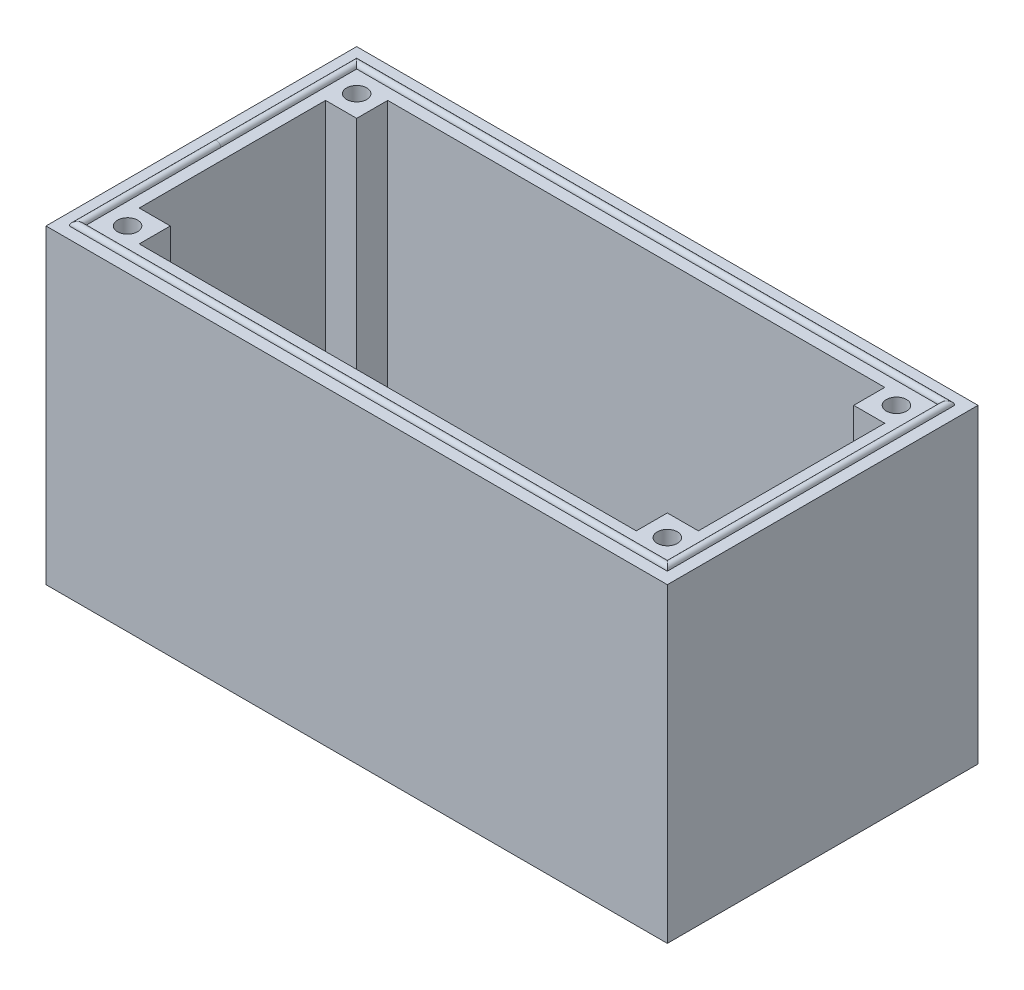
SolidWorks part; units mm, degrees
ref_plane "Piano frontale" through (0, 0, 0) normal (0, 0, 1) x (1, 0, 0)
ref_plane "Piano superiore" through (0, 0, 0) normal (0, 1, 0) x (1, 0, 0)
ref_plane "Piano destro" through (0, 0, 0) normal (1, 0, 0) x (0, 0, -1)
sketch "Schizzo1" plane through (0, 0, 0) normal (0, 0, 1) x (1, 0, 0)
  line L0 (0, 0) -> (0, 20)
  line L1 (0, 20) -> (40, 20)
  line L2 (40, 20) -> (40, 0)
  line L3 (40, 0) -> (0, 0)
  dimension "D1" = 40
  dimension "D2" = 20
extrude "Estrusione-Estrusione1" add sketch "Schizzo1" against normal blind 20
sketch "Schizzo2" plane through (0, 20, 0) normal (0, 1, 0) x (1, 0, 0)
  line L0 (0, 10) -> (40, 10) construction
  line L1 (0, 20) -> (0, 0) construction
  line L2 (40, 20) -> (40, 0) construction
  line L3 (20, 20) -> (20, 0) construction
  line L4 (40, 20) -> (0, 20) construction
  line L5 (40, 0) -> (0, 0) construction
  line L6 (4, 18) -> (4, 16)
  line L7 (36, 2) -> (4, 2)
  line L8 (38, 4) -> (38, 16)
  line L9 (36, 18) -> (4, 18)
  line L10 (2, 4) -> (2, 16)
  line L13 (4, 16) -> (2, 16)
  line L14 (2, 4) -> (4, 4)
  line L15 (4, 4) -> (4, 2)
  line L16 (36, 18) -> (36, 16)
  line L17 (36, 16) -> (38, 16)
  line L18 (38, 4) -> (36, 4)
  line L19 (36, 4) -> (36, 2)
  point P12 (20, 10)
  point P16 (36, 17.1111)
  point P30 (36, 4)
  dimension "D1" = 2
  dimension "D2" = 2
  dimension "D3" = 2
  dimension "D4" = 12
  dimension "D5" = 32
extrude "Taglio-Estrusione1" cut sketch "Schizzo2" against normal blind 20 contours L8 L17 L16 L9 L6 L13 L10 L14 L15 L7 L19 L18
ref_plane "Piano1" through (0, 0, -10) normal (0, 0, 1) x (1, 0, 0)
sketch "Schizzo3" plane through (0, 0, -10) normal (0, 0, 1) x (1, 0, 0)
  line L0 (40, 20) -> (0, 20) construction
  line L1 (0.75, 20) -> (1.25, 20)
  arc A0 (1.25, 20) -> (0.75, 20) centre (1, 20) ccw
  point P0 (1.999, 20)
  dimension "D1" = 0.5
  dimension "D2" = 1
  dimension "D3" = 0.999
sketch "Schizzo4" plane through (0, 20, 0) normal (0, 1, 0) x (1, 0, 0)
  line L0 (0, 10) -> (40, 10) construction
  line L1 (0, 20) -> (0, 0) construction
  line L2 (-11.1375, 10) -> (11.1375, 10) construction
  line L3 (20, 0) -> (20, 20) construction
  line L4 (40, 0) -> (0, 0) construction
  line L5 (40, 20) -> (0, 20) construction
  line L6 (40, 20) -> (40, 0) construction
  line L7 (1, 19) -> (39, 19)
  line L8 (1, 19) -> (1, 1)
  line L9 (1, 1) -> (39, 1)
  line L10 (39, 19) -> (39, 1)
  line L11 (1, 19) -> (39, 1) construction
  line L12 (1, 1) -> (39, 19) construction
  point P12 (20, 10)
  dimension "D1" = 1
  dimension "D2" = 1
  dimension "D3" = 1
sweep "Sweep1" add profiles "Schizzo3" path "Schizzo4"
sketch "Schizzo5" plane through (0, 0, 0) normal (0, -1, 0) x (1, 0, 0)
  line L4 (1, -19) -> (39, -19)
  line L5 (1, -1) -> (1, -19)
  line L6 (39, -1) -> (1, -1)
  line L7 (39, -19) -> (39, -1)
  line L8 (1, -19) -> (39, -19)
  line L9 (1, -1) -> (1, -19)
  line L10 (39, -1) -> (1, -1)
  line L11 (39, -19) -> (39, -1)
  dimension "D1" = 0
sketch "Schizzo6" plane through (0, 0, -10) normal (0, 0, 1) x (1, 0, 0)
  line L0 (39, 0) -> (1, 0) construction
  line L1 (1, 0) -> (39, 0) construction
  line L2 (0, 20) -> (0, 0) construction
  line L3 (0.75, 0) -> (1.25, 0)
  arc A0 (1.25, 0) -> (0.75, 0) centre (1, 0) ccw
  dimension "D1" = 0.5
  dimension "D2" = 1
sweep "Taglia-Sweep1" cut profiles "Schizzo6" path "Schizzo5"
hole_wizard "Foro per Vite M1-1" positions "Schizzo7" profile "Schizzo9" hole size "M1" standard "KS" end condition through all
sketch "Schizzo7" plane through (0, 0, 0) normal (0, -1, 0) x (-1, 0, 0)
  line L4 (-38.75, 1.25) -> (-38.75, 18.75) construction
  line L5 (-38.75, 18.75) -> (-1.25, 18.75) construction
  point P0 (-37.375, 17.375)
  dimension "D1" = 1.375
  dimension "D2" = 1.375
sketch "Schizzo9" plane through (37.375, 0, -17.375) normal (1, 0, 0) x (0, 0, -1)
  line L0 (0, 0) -> (0, 20.25)
  line L1 (0, 20.25) -> (0.65, 20.25)
  line L2 (0.65, 20.25) -> (0.65, 0.025)
  line L3 (0.65, 0.025) -> (0.675, 0)
  line L5 (0.675, 0) -> (0, 0)
  line L6 (-0.65, 0.025) -> (-0.675, 0) construction
  line L11 (0, -6.35) -> (0, 107.95) construction
  dimension "Thru Hole Dia." = 1.3
  dimension "Thru Hole Depth" = 20.25
  dimension "Near C'Sink Dia." = 1.35
  dimension "Near C'Sink Angle" = 90
cosmetic thread "Cosmetic Thread5" parameters "D2"=2.3
mirror "Specchia1" about plane through (0, 0, -10) normal (0, 0, 1) of "Foro per Vite M1-1"
cosmetic thread "Cosmetic Thread6" parameters "D2"=2.3
ref_plane "Piano2" through (20, 0, 0) normal (1, 0, 0) x (0, 0, -1)
mirror "Specchia2" about plane through (20, 0, 0) normal (1, 0, 0) of "Specchia1", "Foro per Vite M1-1"
cosmetic thread "Cosmetic Thread7" parameters "D2"=2.3
cosmetic thread "Cosmetic Thread8" parameters "D2"=2.3
